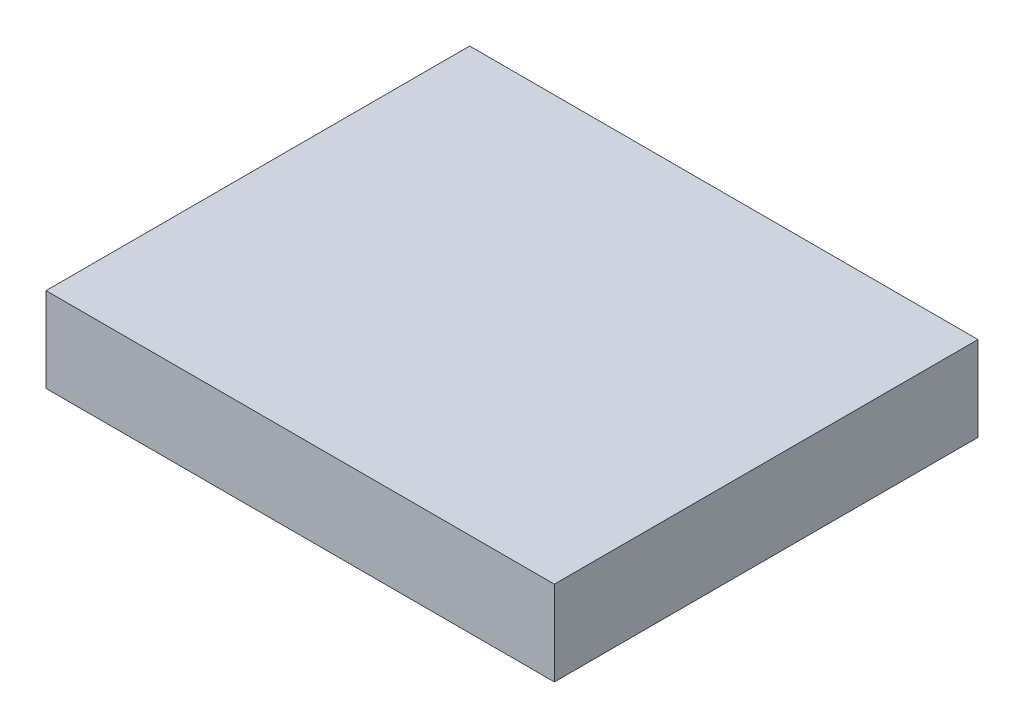
SolidWorks part; units mm, degrees
ref_plane "Front Plane" through (0, 0, 0) normal (0, 0, 1) x (1, 0, 0)
ref_plane "Top Plane" through (0, 0, 0) normal (0, 1, 0) x (1, 0, 0)
ref_plane "Right Plane" through (0, 0, 0) normal (1, 0, 0) x (0, 0, -1)
sketch "Sketch1" plane through (0, 0, 0) normal (0, 1, 0) x (1, 0, 0)
  line L1 (-91.3912, 43.7593) -> (-15.1912, 43.7593)
  line L2 (-91.3912, 43.7593) -> (-91.3912, -19.7407)
  line L3 (-91.3912, -19.7407) -> (-15.1912, -19.7407)
  line L4 (-15.1912, 43.7593) -> (-15.1912, -19.7407)
  dimension "D1" = 76.2
  dimension "D2" = 63.5
extrude "Boss-Extrude1" add sketch "Sketch1" along normal blind 12.7
